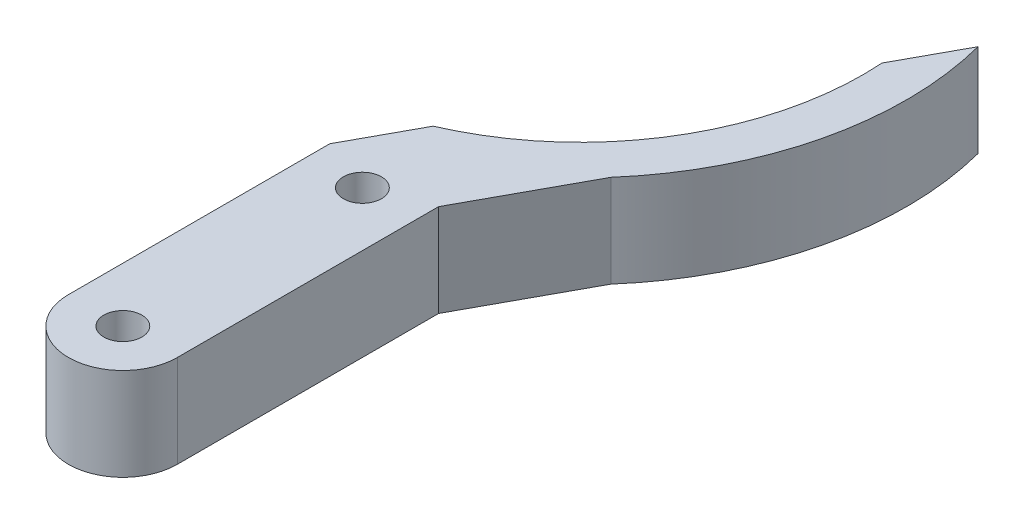
SolidWorks part; units mm, degrees
ref_plane "前视基准面" through (0, 0, 0) normal (0, 0, 1) x (1, 0, 0)
ref_plane "上视基准面" through (0, 0, 0) normal (0, 1, 0) x (1, 0, 0)
ref_plane "右视基准面" through (0, 0, 0) normal (1, 0, 0) x (0, 0, -1)
sketch "草图1" plane through (0, 0, 0) normal (0, 1, 0) x (1, 0, 0)
  line L2 (-5, 0) -> (-5, 24)
  line L4 (5, 0) -> (5, 24)
  line L6 (13.9392, 55.7778) -> (17.0498, 61.4906)
  line L7 (5, 24) -> (10.58, 34.248)
  line L8 (-5, 24) -> (-1.6526, 30.1477)
  circle A0 centre (0, 0) radius 1.75
  circle A1 centre (0, 22) radius 1.75
  arc A2 (10.58, 34.248) -> (17.0498, 61.4906) centre (-12, 54) ccw
  arc A3 (-1.6526, 30.1477) -> (13.9392, 55.7778) centre (-12, 54) ccw
  arc A6 (5, 0) -> (-5, 0) centre (0, 0) cw
  point P29 (0, 0)
  point P32 (10, 0)
  dimension "D3" = 3.5
  dimension "D4" = 22
  dimension "D5" = 30
  dimension "D6" = 26
  dimension "D10" = 10
  dimension "D1" = 10
  dimension "D2" = 24
  dimension "D7" = 7
  dimension "D8" = 7
  dimension "D9" = 32
  dimension "D11" = 30
  dimension "D12" = 24
extrude "凸台-拉伸1" add sketch "草图1" along normal blind 8.5
